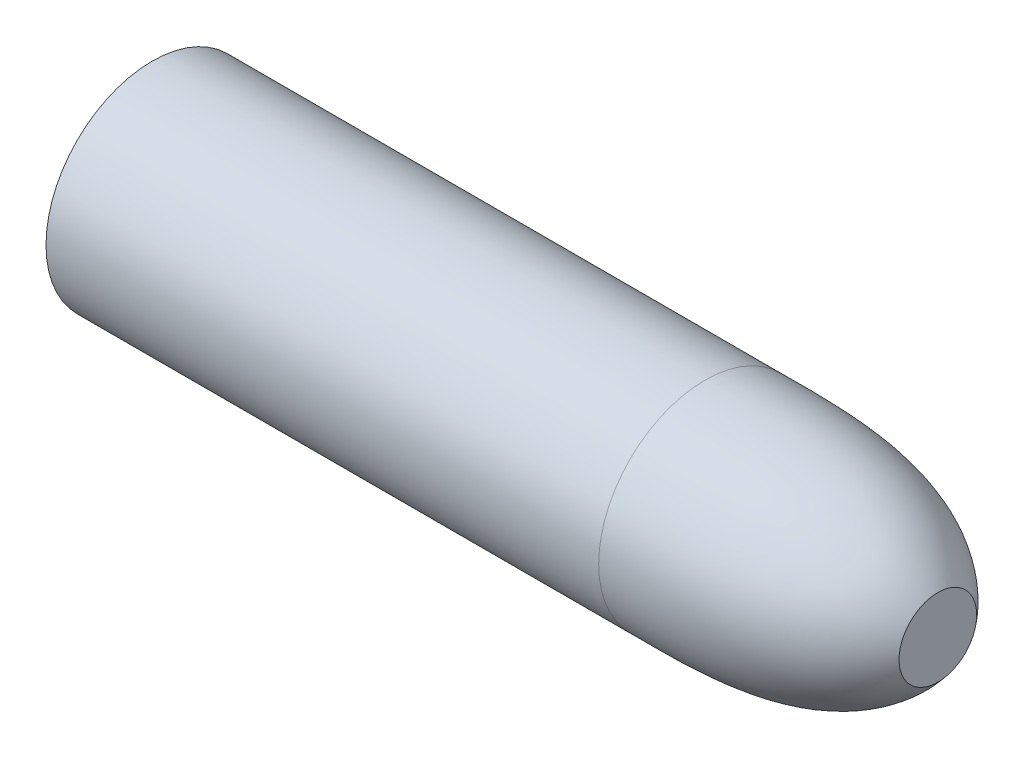
SolidWorks part; units mm, degrees
ref_plane "Front Plane" through (0, 0, 0) normal (0, 0, 1) x (1, 0, 0)
ref_plane "Top Plane" through (0, 0, 0) normal (0, 1, 0) x (1, 0, 0)
ref_plane "Right Plane" through (0, 0, 0) normal (1, 0, 0) x (0, 0, -1)
sketch "Sketch1" plane through (0, 0, 0) normal (0, 0, 1) x (1, 0, 0)
  line L0 (0, 0) -> (257, 0) construction
  line L2 (0, 0) -> (0, 34.75)
  line L3 (0, 34.75) -> (180.8, 34.75)
  line L5 (257, 0) -> (257, 12.7)
  line L6 (0, 0) -> (257, 0)
  spline S0 degree 3 poles (180.8, 34.75) (206.6269, 34.8833) (239.0153, 35.3923) (257, 12.7) knots 0 0 0 0 1 1 1 1
  point P0 (240.1133, 26.2635)
  point P9 (224.997, 40.8179)
  point P11 (201.2383, 43.6021)
  dimension "D5" = 211.8665
  dimension "D1" = 257
  dimension "D2" = 34.75
  dimension "D3" = 180.8
  dimension "D4" = 12.7
  dimension "D6" = 240.1133
  dimension "D7" = 26.2635
  dimension "D8" = 33.7783
revolve "Revolve3" add sketch "Sketch1" angle 360 about L0
